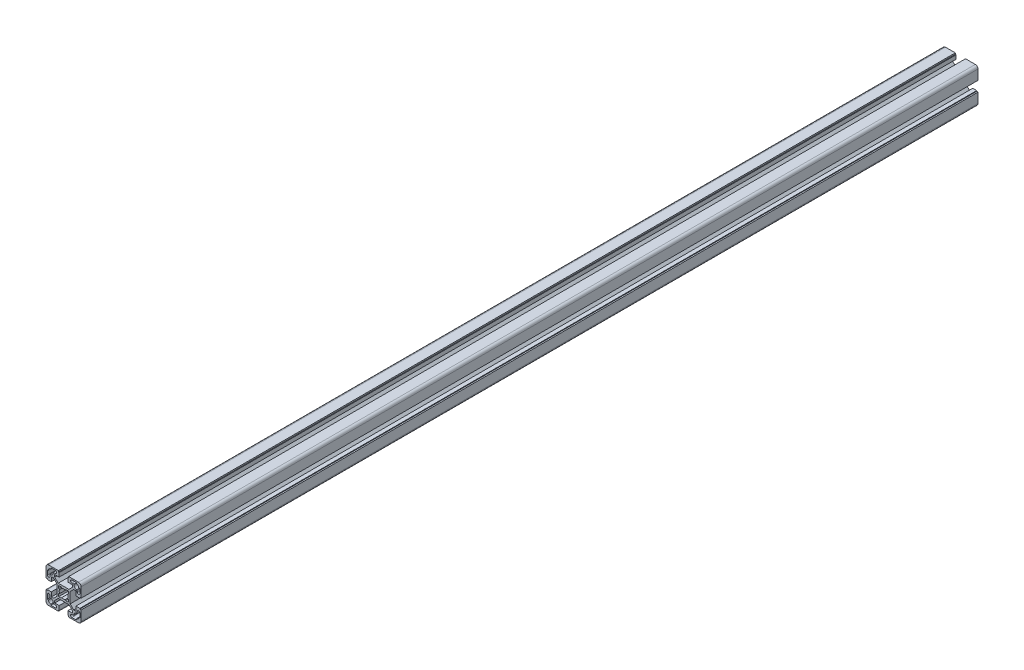
SolidWorks part; units mm, degrees
material "6061 Alloy"
ref_plane "Front Plane" through (0, 0, 0) normal (0, 0, 1) x (1, 0, 0)
ref_plane "Top Plane" through (0, 0, 0) normal (0, 1, 0) x (1, 0, 0)
ref_plane "Right Plane" through (0, 0, 0) normal (1, 0, 0) x (0, 0, -1)
sketch "Sketch1" plane through (0, 0, 0) normal (0, 0, 1) x (1, 0, 0)
  line L0 (5.8, -20) -> (17, -20)
  line L1 (14, -10.05) -> (11.4642, -10.05)
  line L2 (0, -21.1722) -> (0, 18.817) construction
  line L3 (0, 21.1722) -> (0, -18.817) construction
  line L4 (14.5, -18.5) -> (9.5, -18.5)
  line L5 (18.5, 5) -> (14, 5)
  line L6 (6.0858, -7.5) -> (10.05, -11.4642)
  line L7 (20, 5.8) -> (18.5, 5.8)
  line L8 (14, 5) -> (14, 10.05)
  line L9 (18.5, 5.8) -> (18.5, 5)
  line L10 (18.5, 14.5) -> (17.25, 14.5)
  line L11 (14.5, 11.75) -> (15.5, 11.75)
  line L12 (14.5, 17.25) -> (14.5, 18.5)
  line L13 (18.5, 9.5) -> (18.5, 14.5)
  line L14 (15.5, 11.75) -> (15.5, 9.5)
  line L15 (20, 17) -> (20, 5.8)
  line L16 (5.5, 5.5) -> (2.3979, 5.5)
  line L17 (2.3979, 5.5) -> (1.9983, 4.5833)
  line L18 (5.5, 2.3979) -> (5.5, 5.5)
  line L19 (4.5833, 1.9983) -> (5.5, 2.3979)
  line L20 (5, -14) -> (5, -18.5)
  line L21 (11.4642, 10.05) -> (7.5, 6.0858)
  line L22 (-6.0858, 7.5) -> (6.0858, 7.5)
  line L23 (11.75, 15.5) -> (11.75, 14.5)
  line L24 (5, -18.5) -> (5.8, -18.5)
  line L25 (5.8, -18.5) -> (5.8, -20)
  line L26 (10.05, -11.4642) -> (10.05, -14)
  line L27 (10.05, -14) -> (5, -14)
  line L28 (9.5, -15.5) -> (11.75, -15.5)
  line L29 (11.75, -15.5) -> (11.75, -14.5)
  line L30 (9.5, 15.5) -> (11.75, 15.5)
  line L31 (10.05, 14) -> (5, 14)
  line L32 (10.05, 11.4642) -> (10.05, 14)
  line L33 (5.8, 18.5) -> (5.8, 20)
  line L34 (5, 18.5) -> (5.8, 18.5)
  line L35 (7.5, -6.0858) -> (7.5, 6.0858)
  line L36 (5, 14) -> (5, 18.5)
  line L37 (6.0858, 7.5) -> (10.05, 11.4642)
  line L38 (14.5, 18.5) -> (9.5, 18.5)
  line L39 (14, 10.05) -> (11.4642, 10.05)
  line L40 (5.8, 20) -> (17, 20)
  line L41 (-18.5, -5) -> (-14, -5)
  line L42 (-6.0858, -7.5) -> (6.0858, -7.5)
  line L43 (11.4642, -10.05) -> (7.5, -6.0858)
  line L44 (-20, -5.8) -> (-18.5, -5.8)
  line L45 (-14, -5) -> (-14, -10.05)
  line L46 (-18.5, -5.8) -> (-18.5, -5)
  line L47 (-18.5, -14.5) -> (-17.25, -14.5)
  line L48 (4.5833, -1.9983) -> (5.5, -2.3979)
  line L49 (5.5, -2.3979) -> (5.5, -5.5)
  line L50 (2.3979, -5.5) -> (1.9983, -4.5833)
  line L51 (5.5, -5.5) -> (2.3979, -5.5)
  line L52 (-14.5, -11.75) -> (-15.5, -11.75)
  line L53 (-14.5, -17.25) -> (-14.5, -18.5)
  line L54 (-18.5, -9.5) -> (-18.5, -14.5)
  line L55 (-15.5, -11.75) -> (-15.5, -9.5)
  line L56 (-20, -17) -> (-20, -5.8)
  line L57 (-5.5, -5.5) -> (-2.3979, -5.5)
  line L58 (-2.3979, -5.5) -> (-1.9983, -4.5833)
  line L59 (-5.5, -2.3979) -> (-5.5, -5.5)
  line L60 (-4.5833, -1.9983) -> (-5.5, -2.3979)
  line L61 (-11.4642, -10.05) -> (-7.5, -6.0858)
  line L62 (-5.8, 20) -> (-17, 20)
  line L63 (-14, 10.05) -> (-11.4642, 10.05)
  line L64 (-14.5, 18.5) -> (-9.5, 18.5)
  line L65 (-6.0858, 7.5) -> (-10.05, 11.4642)
  line L66 (-5, 14) -> (-5, 18.5)
  line L67 (-7.5, -6.0858) -> (-7.5, 6.0858)
  line L68 (-5, 18.5) -> (-5.8, 18.5)
  line L69 (-5.8, 18.5) -> (-5.8, 20)
  line L70 (-10.05, 11.4642) -> (-10.05, 14)
  line L71 (-10.05, 14) -> (-5, 14)
  line L72 (-9.5, 15.5) -> (-11.75, 15.5)
  line L73 (-11.75, -15.5) -> (-11.75, -14.5)
  line L74 (-9.5, -15.5) -> (-11.75, -15.5)
  line L75 (-10.05, -14) -> (-5, -14)
  line L76 (-10.05, -11.4642) -> (-10.05, -14)
  line L77 (-5.8, -18.5) -> (-5.8, -20)
  line L78 (-5, -18.5) -> (-5.8, -18.5)
  line L79 (-11.75, 15.5) -> (-11.75, 14.5)
  line L80 (-11.4642, 10.05) -> (-7.5, 6.0858)
  line L81 (-5, -14) -> (-5, -18.5)
  line L82 (-4.5833, 1.9983) -> (-5.5, 2.3979)
  line L83 (-5.5, 2.3979) -> (-5.5, 5.5)
  line L84 (-2.3979, 5.5) -> (-1.9983, 4.5833)
  line L85 (-5.5, 5.5) -> (-2.3979, 5.5)
  line L86 (-20, 17) -> (-20, 5.8)
  line L87 (-15.5, 11.75) -> (-15.5, 9.5)
  line L88 (20, -17) -> (20, -5.8)
  line L89 (15.5, -11.75) -> (15.5, -9.5)
  line L90 (18.5, -9.5) -> (18.5, -14.5)
  line L91 (14.5, -17.25) -> (14.5, -18.5)
  line L92 (14.5, -11.75) -> (15.5, -11.75)
  line L93 (18.5, -14.5) -> (17.25, -14.5)
  line L94 (-18.5, 9.5) -> (-18.5, 14.5)
  line L95 (-14.5, 17.25) -> (-14.5, 18.5)
  line L96 (18.5, -5.8) -> (18.5, -5)
  line L97 (14, -5) -> (14, -10.05)
  line L98 (20, -5.8) -> (18.5, -5.8)
  line L99 (18.5, -5) -> (14, -5)
  line L100 (-14.5, 11.75) -> (-15.5, 11.75)
  line L101 (-18.5, 14.5) -> (-17.25, 14.5)
  line L102 (-18.5, 5.8) -> (-18.5, 5)
  line L103 (-14, 5) -> (-14, 10.05)
  line L104 (-20, 5.8) -> (-18.5, 5.8)
  line L105 (-6.0858, -7.5) -> (-10.05, -11.4642)
  line L106 (-18.5, 5) -> (-14, 5)
  line L107 (-14.5, -18.5) -> (-9.5, -18.5)
  line L108 (-20, 0) -> (20.788, 0) construction
  line L109 (-14, -10.05) -> (-11.4642, -10.05)
  line L110 (-5.8, -20) -> (-17, -20)
  arc A0 (14.5, -11.75) -> (11.75, -14.5) centre (14.5, -14.5) ccw
  arc A1 (18.5, 9.5) -> (15.5, 9.5) centre (17, 9.5) cw
  arc A2 (14.5, 17.25) -> (17.25, 14.5) centre (14.5, 14.5) cw
  arc A3 (17, 20) -> (20, 17) centre (17, 17) cw
  arc A4 (-1.9983, 4.5833) -> (1.9983, 4.5833) centre (0, 0) cw
  arc A5 (9.5, 15.5) -> (9.5, 18.5) centre (9.5, 17) cw
  arc A6 (9.5, -15.5) -> (9.5, -18.5) centre (9.5, -17) ccw
  arc A7 (14.5, 11.75) -> (11.75, 14.5) centre (14.5, 14.5) cw
  arc A8 (4.5833, -1.9983) -> (4.5833, 1.9983) centre (0, 0) ccw
  arc A9 (-18.5, -9.5) -> (-15.5, -9.5) centre (-17, -9.5) cw
  arc A10 (-14.5, -17.25) -> (-17.25, -14.5) centre (-14.5, -14.5) cw
  arc A11 (-1.9983, -4.5833) -> (1.9983, -4.5833) centre (0, 0) ccw
  arc A12 (-17, -20) -> (-20, -17) centre (-17, -17) cw
  arc A13 (-4.5833, -1.9983) -> (-4.5833, 1.9983) centre (0, 0) cw
  arc A14 (-14.5, 11.75) -> (-11.75, 14.5) centre (-14.5, 14.5) ccw
  arc A15 (-9.5, -15.5) -> (-9.5, -18.5) centre (-9.5, -17) cw
  arc A16 (-9.5, 15.5) -> (-9.5, 18.5) centre (-9.5, 17) ccw
  arc A17 (-17, 20) -> (-20, 17) centre (-17, 17) ccw
  arc A18 (17, -20) -> (20, -17) centre (17, -17) ccw
  arc A19 (14.5, -17.25) -> (17.25, -14.5) centre (14.5, -14.5) ccw
  arc A20 (18.5, -9.5) -> (15.5, -9.5) centre (17, -9.5) ccw
  arc A21 (-14.5, 17.25) -> (-17.25, 14.5) centre (-14.5, 14.5) ccw
  arc A22 (-18.5, 9.5) -> (-15.5, 9.5) centre (-17, 9.5) ccw
  arc A23 (-14.5, -11.75) -> (-11.75, -14.5) centre (-14.5, -14.5) cw
  point P55 (7.5, 0)
  point P101 (-7.5, 0)
  point P116 (0, -7.5)
  point P149 (0, 7.5)
extrude "Extrude1" add sketch "Sketch1" along normal blind 1020
hole_wizard "M12 Tapped Hole1" [suppressed] positions "3DSketch2" profile "Sketch3" tap size "M12" standard "ISO"
sketch3d "3DSketch2"
  line L0 (-20, 17, 0) -> (-20, 5.8, 0) construction
  line L1 (-5.8, 20, 0) -> (-17, 20, 0) construction
  line L2 (-5.8, 20, 200) -> (-17, 20, 200) construction
  line L3 (-20, 17, 200) -> (-20, 5.8, 200) construction
  point P0 (0, 0, 200)
  point P2 (0, 0, 0)
  dimension "D1" = 20
  dimension "D2" = 20
  dimension "D3" = 20
  dimension "D4" = 20
sketch "Sketch3" plane through (0, 0, 200) normal (1, 0, 0) x (0, -1, 0)
  line L0 (0, 0) -> (0, 35.8144)
  line L1 (0, 35.8144) -> (5.1, 32.75)
  line L2 (5.1, 32.75) -> (5.1, 0.925)
  line L3 (5.1, 0.925) -> (6.025, 0)
  line L5 (6.025, 0) -> (0, 0)
  line L6 (-5.1, 0.925) -> (-6.025, 0) construction
  line L10 (0, 35.8144) -> (-5.1, 32.75) construction
  line L11 (0, -6.35) -> (0, 107.95) construction
  dimension "Tap Drill Dia." = 10.2
  dimension "Tap Drill Depth" = 32.75
  dimension "Near C'Sink Dia." = 12.05
  dimension "Near C'Sink Angle" = 90
  dimension "Drill Angle" = 118
cosmetic thread "Hole Thread1" [suppressed] parameters "D1"=24, "D2"=12
cosmetic thread "Filettatura del foro1" [suppressed] parameters "D1"=24, "D2"=12
hole_wizard "Ø9.8 (9.8) Diameter Hole1" [suppressed] positions "3DSketch3" profile "Sketch4" hole size "Ø9.8" standard "ISO"
sketch3d "3DSketch3"
  line L0 (-5.8, 20, 200) -> (-17, 20, 200) construction
  line L1 (20, -17, 200) -> (20, -5.8, 200) construction
  line L2 (17, 20, 0) -> (5.8, 20, 0) construction
  line L3 (20, -17, 0) -> (20, -5.8, 0) construction
  point P0 (0, 20, 184)
  point P2 (20, 0, 184)
  point P4 (0, 20, 16)
  point P6 (20, 0, 16)
  dimension "D1" = 16
  dimension "D2" = 20
  dimension "D3" = 20
  dimension "D4" = 16
  dimension "D5" = 16
  dimension "D6" = 16
sketch "Sketch4" plane through (0, 20, 184) normal (1, 0, 0) x (0, 0, 1)
  line L0 (0, 0) -> (0, 40)
  line L1 (0, 40) -> (4.9, 40)
  line L2 (4.9, 40) -> (4.9, 0)
  line L5 (4.9, 0) -> (0, 0)
  line L11 (0, -6.35) -> (0, 107.95) construction
  dimension "Thru Hole Dia." = 9.8
  dimension "Thru Hole Depth" = 40
hole_wizard "Ø17.0 (17) Diameter Hole1" [suppressed] positions "3DSketch4" profile "Sketch5" hole size "Ø17.0" standard "ISO"
sketch3d "3DSketch4"
  line L0 (-5.8, 20, 200) -> (-17, 20, 200) construction
  line L1 (-5.8, 20, 0) -> (-17, 20, 0) construction
  point P0 (0, 20, 177.5)
  point P2 (0, 20, 22.5)
  dimension "D1" = 20
  dimension "D2" = 22.5
  dimension "D3" = 22.5
sketch "Sketch5" plane through (0, 20, 177.5) normal (1, 0, 0) x (0, 0, 1)
  line L0 (0, 0) -> (0, 40)
  line L1 (0, 40) -> (8.5, 40)
  line L2 (8.5, 40) -> (8.5, 0)
  line L5 (8.5, 0) -> (0, 0)
  line L11 (0, -6.35) -> (0, 107.95) construction
  dimension "Thru Hole Dia." = 17
  dimension "Thru Hole Depth" = 40
